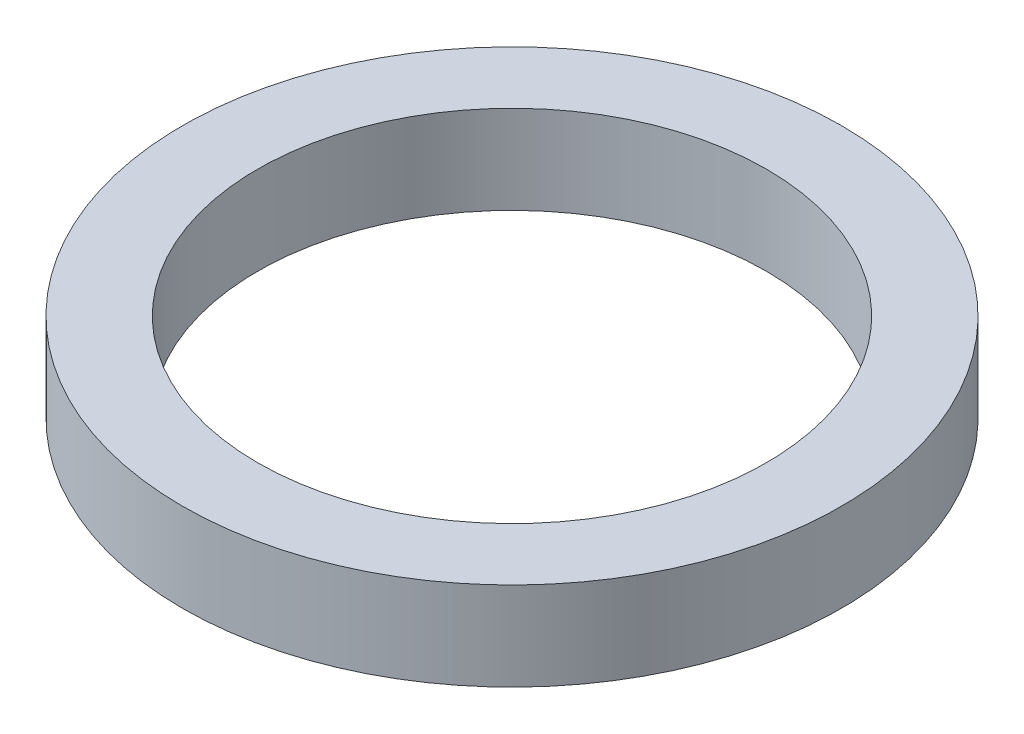
SolidWorks part; units mm, degrees
ref_plane "Front Plane" through (0, 0, 0) normal (0, 0, 1) x (1, 0, 0)
ref_plane "Top Plane" through (0, 0, 0) normal (0, 1, 0) x (1, 0, 0)
ref_plane "Right Plane" through (0, 0, 0) normal (1, 0, 0) x (0, 0, -1)
sketch "Sketch1" plane through (0, 0, 0) normal (0, 1, 0) x (1, 0, 0)
  circle A0 centre (0, 0) radius 7.45
  circle A1 centre (0, 0) radius 5.75
  dimension "D1" = 14.9
  dimension "D2" = 11.5
extrude "Boss-Extrude1" add sketch "Sketch1" along normal blind 2
